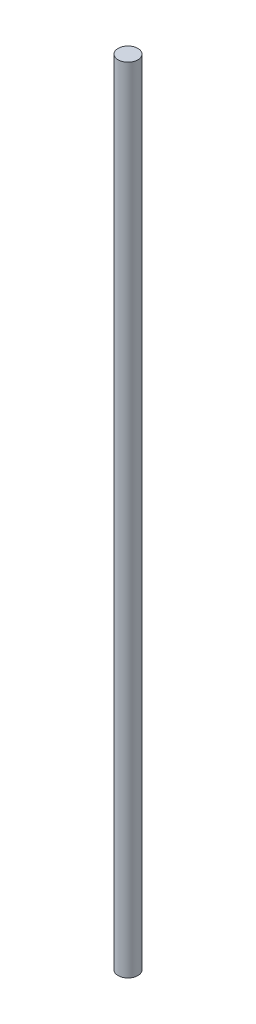
SolidWorks part; units mm, degrees
ref_plane "前视基准面" through (0, 0, 0) normal (0, 0, 1) x (1, 0, 0)
ref_plane "上视基准面" through (0, 0, 0) normal (0, 1, 0) x (1, 0, 0)
ref_plane "右视基准面" through (0, 0, 0) normal (1, 0, 0) x (0, 0, -1)
other "Configuration Table"
sketch "草图1" plane through (0, 0, 0) normal (0, 1, 0) x (1, 0, 0)
  circle A0 centre (0, 0) radius 1.5
  dimension "D1" = 3
extrude "凸台-拉伸1" add sketch "草图1" along normal blind 120 contours A0
